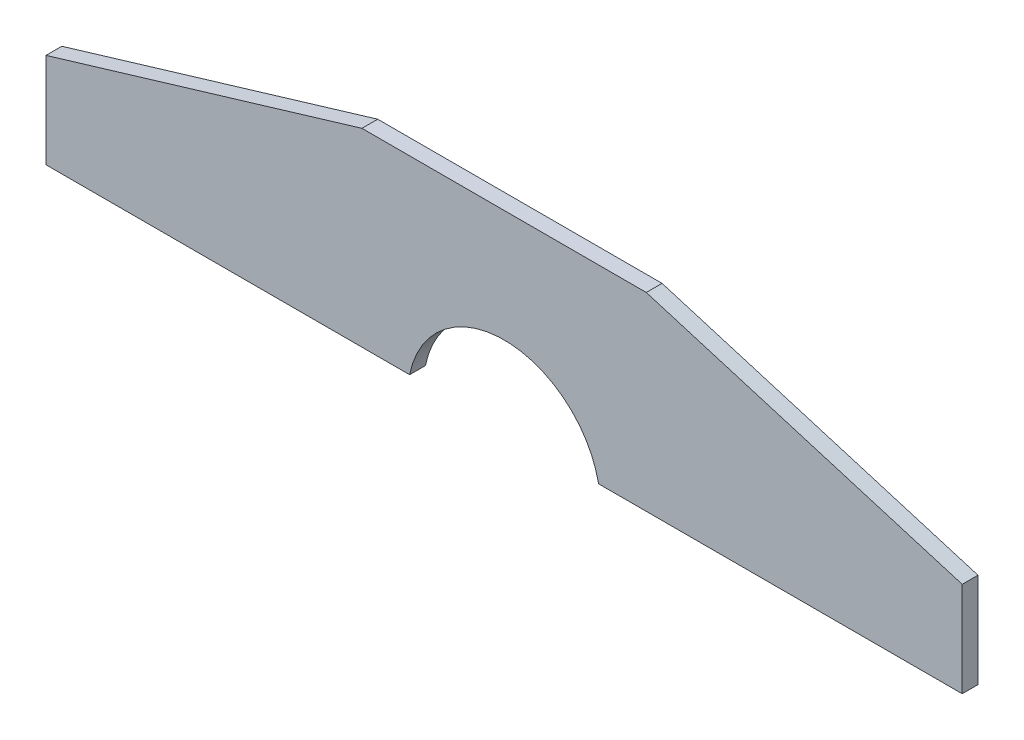
SolidWorks part; units mm, degrees
material "CK45"
ref_plane "Front Plane" through (0, 0, 0) normal (0, 0, 1) x (1, 0, 0)
ref_plane "Top Plane" through (0, 0, 0) normal (0, 1, 0) x (1, 0, 0)
ref_plane "Right Plane" through (0, 0, 0) normal (1, 0, 0) x (0, 0, -1)
sketch "Sketch1" plane through (0, 0, 0) normal (0, 0, 1) x (1, 0, 0)
  line L0 (-145, 36) -> (-45, 66)
  line L1 (-145, 6) -> (-29.904, 6)
  line L2 (-145, 6) -> (-145, 36)
  line L3 (-45, 66) -> (45, 66)
  line L4 (145, 6) -> (145, 36)
  line L5 (45, 66) -> (145, 36)
  line L6 (29.904, 6) -> (145, 6)
  arc A0 (29.904, 6) -> (-29.904, 6) centre (0, 0) ccw
  point P5 (0, 66)
  dimension "D1" = 61
  dimension "D2" = 290
  dimension "D3" = 90
  dimension "D4" = 30
  dimension "D5" = 60
  dimension "D6" = 6
extrude "Boss-Extrude1" add sketch "Sketch1" along normal blind 5
